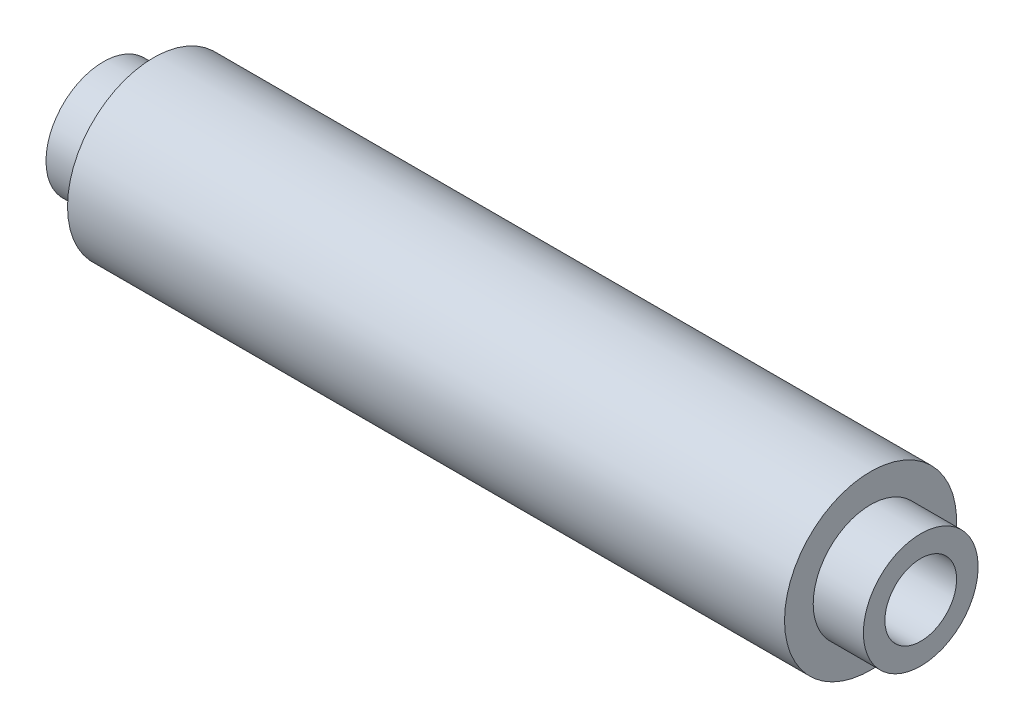
SolidWorks part; units mm, degrees
ref_plane "Front Plane" through (0, 0, 0) normal (0, 0, 1) x (1, 0, 0)
ref_plane "Top Plane" through (0, 0, 0) normal (0, 1, 0) x (1, 0, 0)
ref_plane "Right Plane" through (0, 0, 0) normal (1, 0, 0) x (0, 0, -1)
sketch "Sketch1" plane through (0, 0, 0) normal (0, 0, 1) x (1, 0, 0)
  line L0 (0, 0) -> (146.4006, 0) construction
  line L1 (0, 2.5) -> (20, 2.5)
  line L2 (57, 2.5) -> (57, 4)
  line L3 (57, 4) -> (53.5, 4)
  line L4 (53.5, 4) -> (53.5, 6)
  line L5 (53.5, 6) -> (3.5, 6)
  line L6 (3.5, 6) -> (3.5, 4)
  line L7 (3.5, 4) -> (0, 4)
  line L8 (0, 4) -> (0, 2.5)
  line L9 (20, 2.5) -> (20, 0)
  line L10 (20, 0) -> (37, 0)
  line L11 (37, 0) -> (37, 2.5)
  line L12 (37, 2.5) -> (57, 2.5)
  point P11 (3.5, 5)
  dimension "D1" = 50
  dimension "D2" = 2.5
  dimension "D3" = 1.5
  dimension "D4" = 3.5
  dimension "D5" = 20
  dimension "D6" = 2
revolve "Revolve1" add sketch "Sketch1" angle 360 about L0
